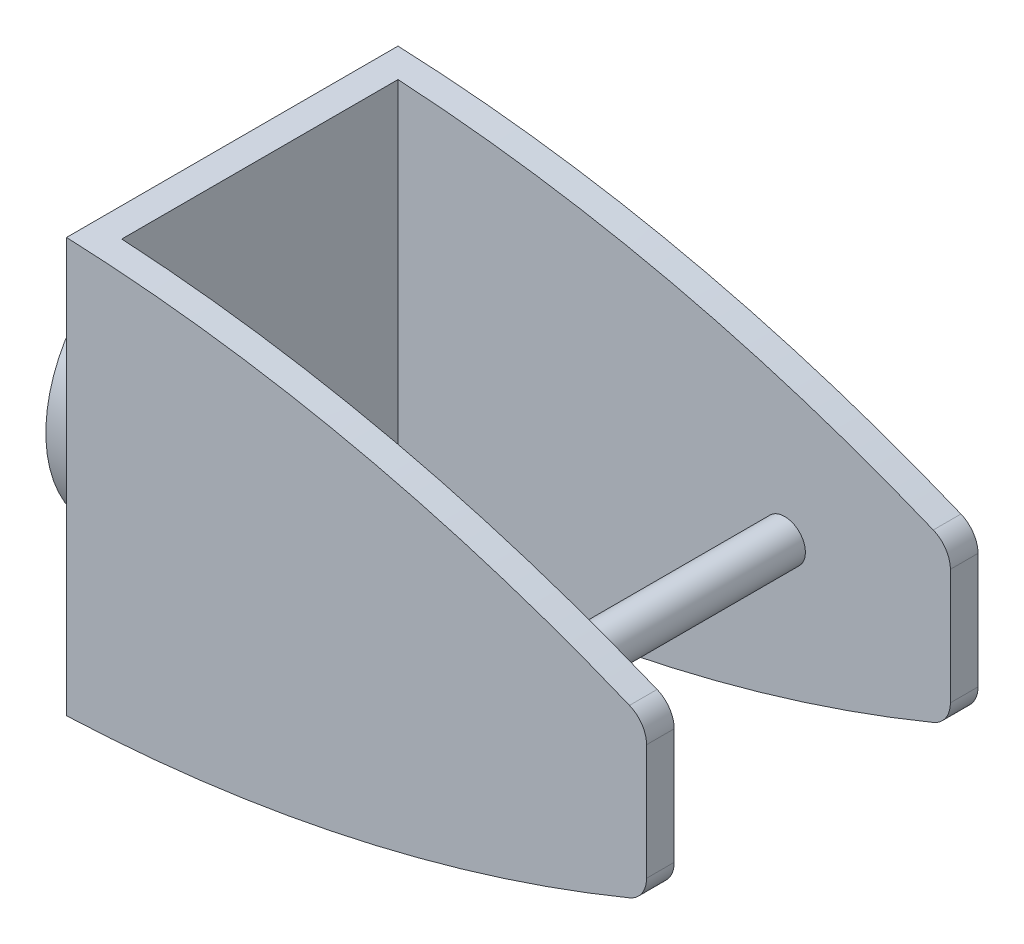
SolidWorks part; units mm, degrees
ref_plane "前视基准面" through (0, 0, 0) normal (0, 0, 1) x (1, 0, 0)
ref_plane "上视基准面" through (0, 0, 0) normal (0, 1, 0) x (1, 0, 0)
ref_plane "右视基准面" through (0, 0, 0) normal (1, 0, 0) x (0, 0, -1)
sketch "草图1" plane through (0, 0, 0) normal (1, 0, 0) x (0, 0, -1)
  circle A0 centre (0, 0) radius 10
  dimension "D1" = 20
extrude "凸台-拉伸1" add sketch "草图1" along normal blind 3.5
sketch "草图2" plane through (3.5, 0, 0) normal (1, 0, 0) x (0, 0, -1)
  line L1 (-12, 15) -> (12, 15)
  line L2 (-12, 15) -> (-12, -15)
  line L3 (-12, -15) -> (12, -15)
  line L4 (12, 15) -> (12, -15)
  dimension "D1" = 24
  dimension "D2" = 12
  dimension "D3" = 30
  dimension "D4" = 15
extrude "凸台-拉伸2" add sketch "草图2" along normal blind 2
sketch "草图3" plane through (5.5, 0, 0) normal (1, 0, 0) x (0, 0, -1)
  line L0 (-12, -15) -> (12, -15) construction
  line L1 (12, 15) -> (10, 15)
  line L2 (12, 15) -> (12, -15)
  line L3 (12, -15) -> (10, -15)
  line L4 (10, 15) -> (10, -15)
  line L6 (-12, 15) -> (-10, 15)
  line L7 (-12, 15) -> (-12, -15)
  line L8 (-12, -15) -> (-10, -15)
  line L9 (-10, 15) -> (-10, -15)
  dimension "D1" = 2
  dimension "D2" = 2
extrude "凸台-拉伸3" add sketch "草图3" along normal blind 40
sketch "草图4" plane through (0, 0, 12) normal (0, 0, 1) x (1, 0, 0)
  line L0 (45.5, 15) -> (45.5, -15) construction
  line L1 (45.5, 5.5171) -> (45.5, 15)
  line L2 (45.5, 15) -> (3.5, 15)
  line L3 (3.5, -15) -> (45.5, -15)
  line L4 (45.5, -15) -> (45.5, -5.5171)
  arc A0 (3.5, 15) -> (45.5, 5.5171) centre (-1.5, -104.8958) cw
  arc A1 (3.5, -15) -> (45.5, -5.5171) centre (-1.5, 104.8958) ccw
  dimension "D1" = 120
  dimension "D2" = 120
  dimension "D3" = 1.5
extrude "切除-拉伸1" cut sketch "草图4" against normal blind 40
sketch "草图5" plane through (0, 0, 12) normal (0, 0, 1) x (1, 0, 0)
  line L0 (45.5, 5.5171) -> (45.5, -5.5171) construction
  circle A0 centre (33.5, 0) radius 1.5
  dimension "D1" = 3
  dimension "D2" = 12
fillet "圆角1" radius 2 4 edges at (45.5, -5.5171, 11) (45.5, -5.5171, -11) (45.5, 5.5171, -11) (45.5, 5.5171, 11)
extrude "凸台-拉伸4" add sketch "草图5" against normal up to surface (24 mm away) contours A0 up to face at (31.3121, 0, -12)
